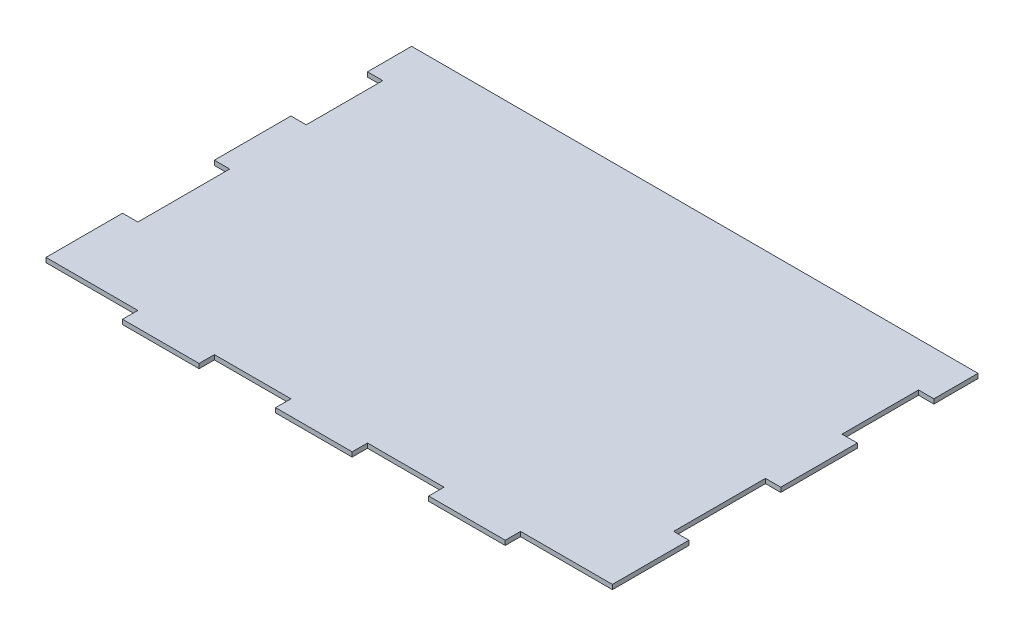
SolidWorks part; units mm, degrees
material "아크릴(내충격성)"
ref_plane "정면" through (0, 0, 0) normal (0, 0, 1) x (1, 0, 0)
ref_plane "윗면" through (0, 0, 0) normal (0, 1, 0) x (1, 0, 0)
ref_plane "우측면" through (0, 0, 0) normal (1, 0, 0) x (0, 0, -1)
sketch "스케치1" plane through (0, 0, 0) normal (0, 1, 0) x (1, 0, 0)
  line L0 (0, 117.995) -> (0, -227.1535) construction
  line L1 (185, 89.4059) -> (-185, 89.4059)
  line L2 (-185, 89.4059) -> (-185, 60.5659)
  line L3 (-125, -159.4341) -> (-75, -159.4341)
  line L4 (-175, 89.4059) -> (-175, -159.4341) construction
  line L5 (-185, -149.4341) -> (185, -149.4341) construction
  line L6 (-25, -159.4341) -> (25, -159.4341)
  line L7 (-175, -149.4341) -> (-185, -149.4341)
  line L8 (-185, -149.4341) -> (-185, -99.4341)
  line L9 (-185, -99.4341) -> (-175, -99.4341)
  line L10 (-175, -99.4341) -> (-175, -39.4341)
  line L11 (-175, -39.4341) -> (-185, -39.4341)
  line L12 (-185, -39.4341) -> (-185, 10.5659)
  line L13 (-185, 10.5659) -> (-175, 10.5659)
  line L14 (-175, 10.5659) -> (-175, 60.5659)
  line L15 (-175, 60.5659) -> (-185, 60.5659)
  line L16 (-185, 10.5659) -> (-185, -39.4341)
  line L17 (-185, -99.4341) -> (-185, -149.4341)
  line L18 (175, 89.4059) -> (175, -159.4341) construction
  line L19 (185, -99.4341) -> (185, -149.4341)
  line L20 (185, 10.5659) -> (185, -39.4341)
  line L21 (175, 60.5659) -> (185, 60.5659)
  line L22 (175, 10.5659) -> (175, 60.5659)
  line L23 (185, 10.5659) -> (175, 10.5659)
  line L24 (185, -39.4341) -> (185, 10.5659)
  line L25 (175, -39.4341) -> (185, -39.4341)
  line L26 (175, -99.4341) -> (175, -39.4341)
  line L27 (185, -99.4341) -> (175, -99.4341)
  line L28 (185, -149.4341) -> (185, -99.4341)
  line L29 (175, -149.4341) -> (185, -149.4341)
  line L31 (185, 89.4059) -> (185, 60.5659)
  line L32 (-175, -149.4341) -> (-125, -149.4341)
  line L33 (-125, -149.4341) -> (-125, -159.4341)
  line L34 (-75, -159.4341) -> (-75, -149.4341)
  line L35 (-75, -149.4341) -> (-25, -149.4341)
  line L36 (-25, -149.4341) -> (-25, -159.4341)
  line L37 (25, -159.4341) -> (25, -149.4341)
  line L38 (25, -149.4341) -> (75, -149.4341)
  line L39 (75, -149.4341) -> (75, -159.4341)
  line L40 (125, -159.4341) -> (125, -149.4341)
  line L41 (125, -149.4341) -> (175, -149.4341)
  line L42 (75, -159.4341) -> (125, -159.4341)
  point P18 (0, -149.4341)
  point P31 (0, -159.4341)
  point P32 (0, 89.4059)
  dimension "D1" = 185
  dimension "D2" = 248.84
  dimension "D3" = 10
  dimension "D4" = 10
  dimension "D5" = 50
  dimension "D6" = 60
  dimension "D7" = 50
  dimension "D8" = 50
  dimension "D9" = 50
  dimension "D10" = 50
  dimension "D11" = 50
  dimension "D12" = 50
  dimension "D13" = 50
  dimension "D14" = 50
extrude "보스-돌출1" add sketch "스케치1" along normal blind 3
